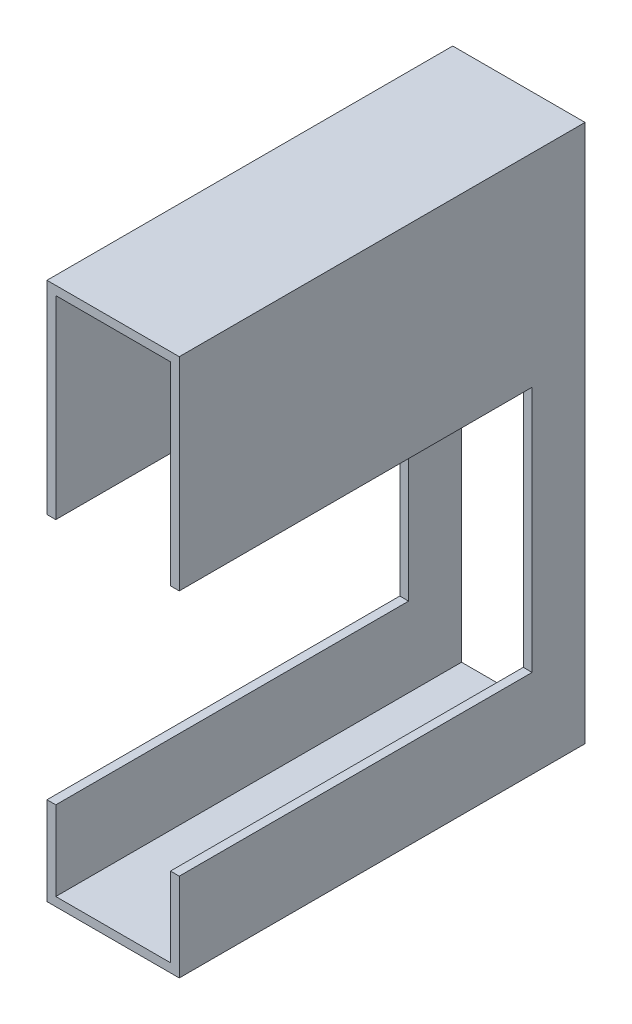
SolidWorks part; units mm, degrees
ref_plane "Front Plane" through (0, 0, 0) normal (0, 0, 1) x (1, 0, 0)
ref_plane "Top Plane" through (0, 0, 0) normal (0, 1, 0) x (1, 0, 0)
ref_plane "Right Plane" through (0, 0, 0) normal (1, 0, 0) x (0, 0, -1)
sketch "Sketch1" plane through (0, 0, 0) normal (0, 0, 1) x (1, 0, 0)
  line L0 (-37.5, 152.5) -> (37.5, 152.5)
  line L1 (-32.5, 147.5) -> (32.5, 147.5)
  line L2 (-32.5, 147.5) -> (-32.5, -147.5)
  line L3 (-32.5, -147.5) -> (32.5, -147.5)
  line L4 (32.5, 147.5) -> (32.5, -147.5)
  line L5 (-32.5, 147.5) -> (32.5, -147.5) construction
  line L6 (-32.5, -147.5) -> (32.5, 147.5) construction
  line L7 (37.5, 152.5) -> (37.5, -152.5)
  line L8 (-37.5, -152.5) -> (37.5, -152.5)
  line L9 (-37.5, 152.5) -> (-37.5, -152.5)
  point P0 (0, 0)
  dimension "D1" = 295
  dimension "D2" = 65
  dimension "D3" = 5
extrude "Boss-Extrude1" add sketch "Sketch1" along normal blind 230
sketch "Sketch2" plane through (37.5, 0, 0) normal (1, 0, 0) x (0, 0, -1)
  line L0 (-230, -152.5) -> (0, -152.5) construction
  line L6 (-230, -152.5) -> (-230, 152.5) construction
  line L8 (-30, 37.5) -> (-230, 37.5)
  line L9 (-30, 37.5) -> (-30, -102.5)
  line L10 (-30, -102.5) -> (-230, -102.5)
  line L11 (-230, 37.5) -> (-230, -102.5)
  line L12 (-30, 37.5) -> (-230, -102.5) construction
  line L13 (-30, -102.5) -> (-230, 37.5) construction
  point P4 (-130, -32.5)
  dimension "D1" = 200
  dimension "D2" = 140
  dimension "D3" = 50
extrude "Cut-Extrude1" cut sketch "Sketch2" against normal through all
